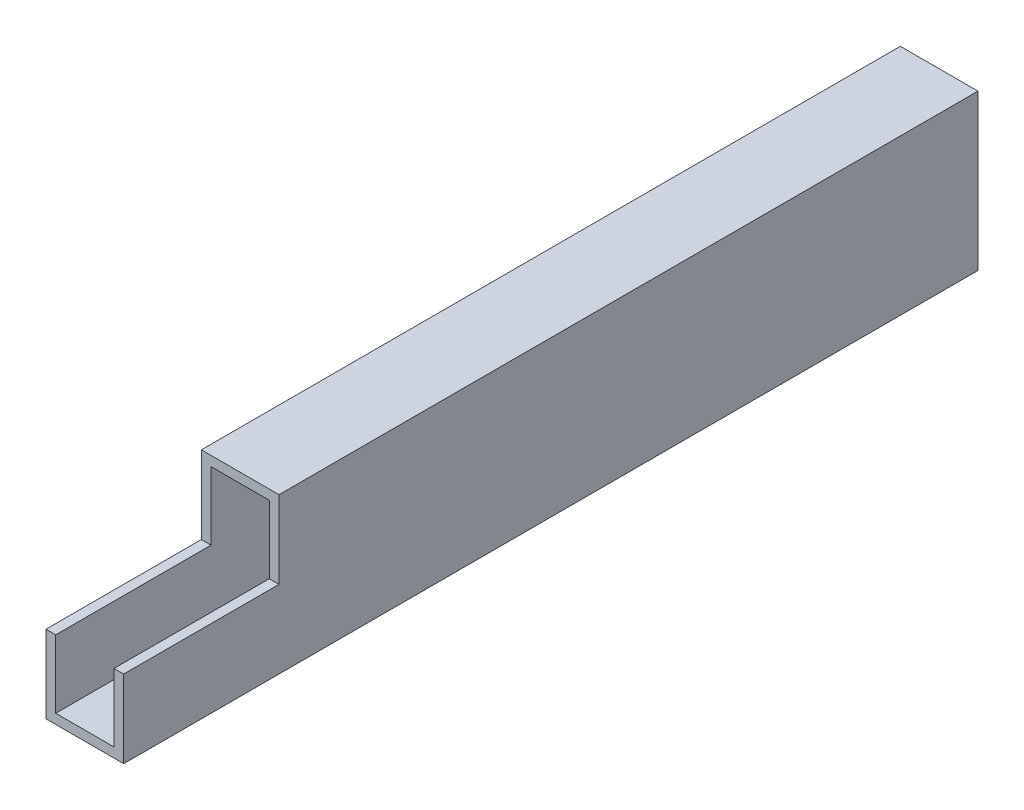
SolidWorks part; units mm, degrees
ref_plane "Front Plane" through (0, 0, 0) normal (0, 0, 1) x (1, 0, 0)
ref_plane "Top Plane" through (0, 0, 0) normal (0, 1, 0) x (1, 0, 0)
ref_plane "Right Plane" through (0, 0, 0) normal (1, 0, 0) x (0, 0, -1)
sketch "Sketch1" plane through (0, 0, 0) normal (0, 0, 1) x (1, 0, 0)
  line L1 (0, 0) -> (25.4, 0)
  line L2 (0, 0) -> (0, -50.8)
  line L3 (0, -50.8) -> (25.4, -50.8)
  line L4 (25.4, 0) -> (25.4, -50.8)
  line L5 (3.175, -3.175) -> (22.225, -3.175)
  line L6 (3.175, -3.175) -> (3.175, -47.625)
  line L7 (3.175, -47.625) -> (22.225, -47.625)
  line L8 (22.225, -3.175) -> (22.225, -47.625)
  dimension "D1" = 50.8
  dimension "D2" = 25.4
  dimension "D3" = 3.175
  dimension "D4" = 3.175
  dimension "D5" = 3.175
  dimension "D6" = 3.175
extrude "Boss-Extrude1" add sketch "Sketch1" along normal blind 279.4
sketch "Sketch2" plane through (25.4, 0, 0) normal (1, 0, 0) x (0, 0, -1)
  line L1 (-279.4, 0) -> (-228.6, 0)
  line L2 (-279.4, 0) -> (-279.4, -25.4)
  line L3 (-279.4, -25.4) -> (-228.6, -25.4)
  line L4 (-228.6, 0) -> (-228.6, -25.4)
  dimension "D1" = 25.4
  dimension "D2" = 50.8
extrude "Cut-Extrude1" cut sketch "Sketch2" against normal up to surface (25.4 mm away) up to face at (0, -25.4, 139.7)
